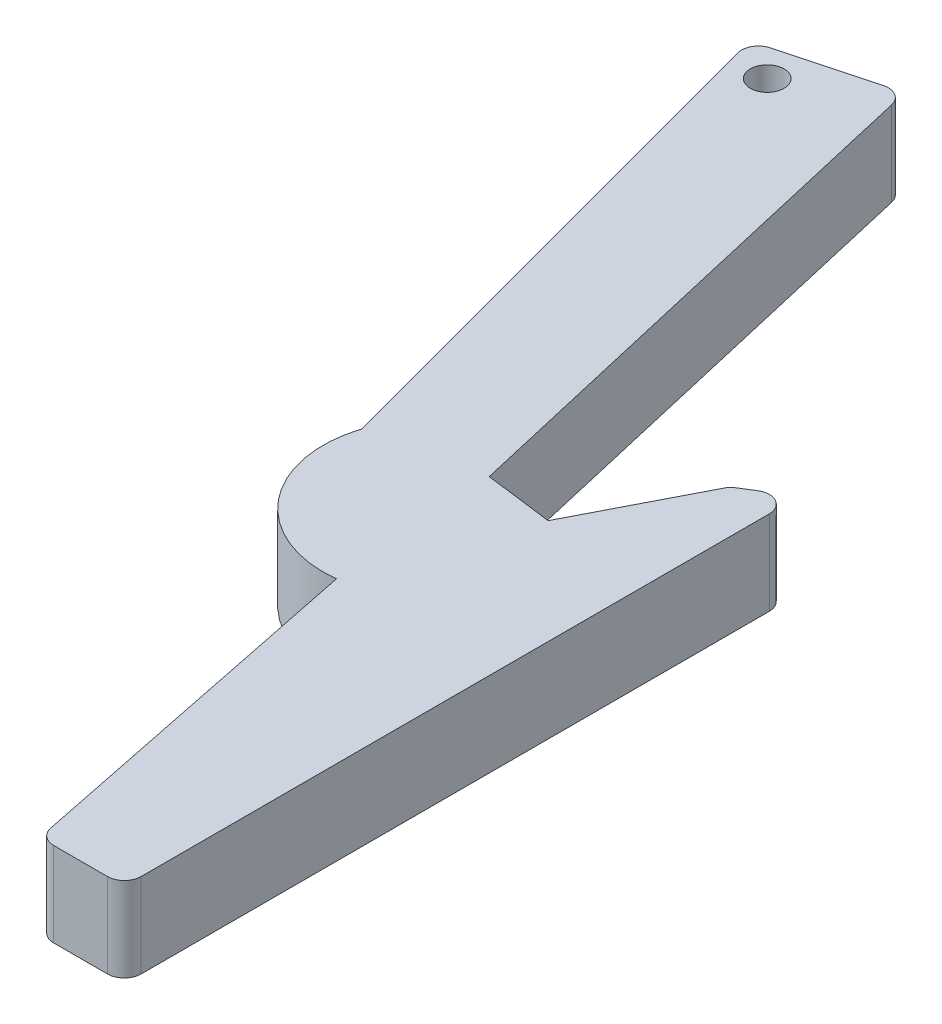
SolidWorks part; units mm, degrees
ref_plane "Front Plane" through (0, 0, 0) normal (0, 0, 1) x (1, 0, 0)
ref_plane "Top Plane" through (0, 0, 0) normal (0, 1, 0) x (1, 0, 0)
ref_plane "Right Plane" through (0, 0, 0) normal (1, 0, 0) x (0, 0, -1)
sketch "Sketch1" plane through (0, 0, 0) normal (0, 1, 0) x (1, 0, 0)
  line L0 (-11.2808, 8.0057) -> (12.6555, 8.0057) construction
  line L1 (5.3871, 8.0057) -> (-9.1018, 4.1235)
  line L2 (-9.1018, 4.1235) -> (7.7214, -58.6617)
  line L3 (5.3871, 8.0057) -> (20.1627, -55.9943)
  line L4 (20.1627, -55.9943) -> (28.1627, -57.0296)
  line L5 (28.1627, -57.0296) -> (35.4796, -42.8007)
  line L6 (35.4796, -42.8007) -> (40.5699, -39.6244)
  line L7 (40.5699, -39.6244) -> (40.5699, -119.6244)
  line L8 (40.5699, -119.6244) -> (30.5699, -119.6244)
  line L9 (30.5699, -119.6244) -> (21.6002, -75.5275)
  arc A0 (21.6002, -75.5275) -> (7.7214, -58.6617) centre (20.1062, -62.6136) cw
  dimension "D12" = 13
  dimension "D1" = 15
  dimension "D2" = 15
  dimension "D3" = 90
  dimension "D4" = 88
  dimension "D5" = 65
  dimension "D6" = 64
  dimension "D7" = 8
  dimension "D8" = 16
  dimension "D9" = 6
  dimension "D10" = 80
  dimension "D11" = 10
  dimension "D13" = 45
extrude "Boss-Extrude1" add sketch "Sketch1" along normal blind 10
sketch "Sketch2" plane through (0, 10, 0) normal (0, 1, 0) x (1, 0, 0)
  line L0 (-9.1018, 4.1235) -> (7.7214, -58.6617) construction
  line L1 (5.3871, 8.0057) -> (-9.1018, 4.1235) construction
  circle A0 centre (-4.2028, 1.295) radius 2
  dimension "D3" = 4
  dimension "D1" = 4
  dimension "D2" = 4
extrude "Cut-Extrude1" cut sketch "Sketch2" against normal through all
fillet "Fillet1" radius 2 6 edges at (40.5699, 5, 119.6244) (30.5699, 5, 119.6244) (40.5699, 5, 39.6244) (35.4796, 5, 42.8007) (5.3871, 5, -8.0057) (-9.1018, 5, -4.1235)
scale "Ölçek1" scale about centroid uniform scaling yes scale factor 2
scale "Ölçek2" bodies to scale 103 scale about centroid uniform scaling yes scale factor 0.4
